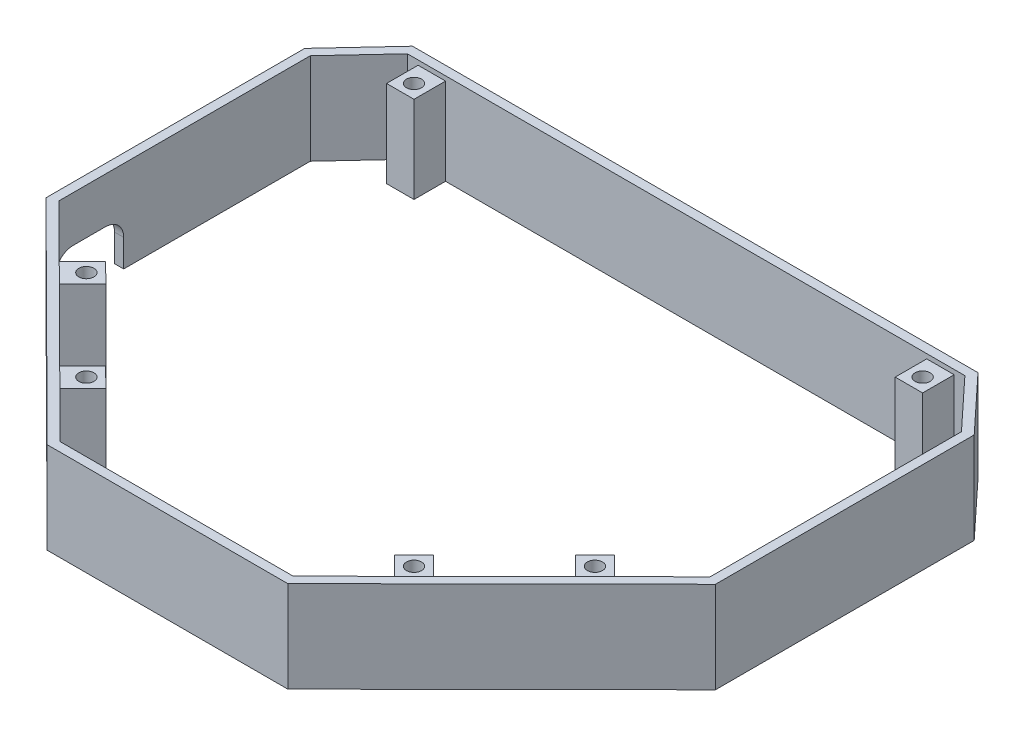
SolidWorks part; units mm, degrees
ref_plane "Front Plane" through (0, 0, 0) normal (0, 0, 1) x (1, 0, 0)
ref_plane "Top Plane" through (0, 0, 0) normal (0, 1, 0) x (1, 0, 0)
ref_plane "Right Plane" through (0, 0, 0) normal (1, 0, 0) x (0, 0, -1)
sketch "Sketch1" plane through (0, 0, 0) normal (0, 1, 0) x (1, 0, 0)
  line L0 (-61, 38.5) -> (61, 38.5)
  line L1 (-25.5, -73) -> (25.5, -73)
  line L2 (-25.5, -73) -> (-71.25, -27.5)
  line L3 (-71.25, -27.5) -> (-71.25, 27.5)
  line L4 (-71.25, 27.5) -> (-61, 38.5)
  line L5 (25.5, -73) -> (71.25, -27.5)
  line L6 (71.25, -27.5) -> (71.25, 27.5)
  line L7 (71.25, 27.5) -> (61, 38.5)
  line L8 (-61.8701, 40.5) -> (61.8701, 40.5)
  line L9 (61.8701, 40.5) -> (73.25, 28.2874)
  line L10 (73.25, 28.2874) -> (73.25, -28.3316)
  line L11 (73.25, -28.3316) -> (26.3252, -75)
  line L12 (26.3252, -75) -> (-26.3252, -75)
  line L13 (-26.3252, -75) -> (-73.25, -28.3316)
  line L14 (-73.25, -28.3316) -> (-73.25, 28.2874)
  line L15 (-73.25, 28.2874) -> (-61.8701, 40.5)
  point P2 (0, 38.5)
  point P6 (0, -73)
  point P22 (-71.25, 0)
  dimension "D1" = 122
  dimension "D2" = 51
  dimension "D3" = 111.5
  dimension "D4" = 55
  dimension "D5" = 55
  dimension "D6" = 142.5
  dimension "D7" = 11
  dimension "D8" = 11
  dimension "D9" = 71.25
  dimension "D10" = 2
  dimension "D11" = 2
  dimension "D12" = 2
  dimension "D13" = 2
  dimension "D14" = 2
  dimension "D15" = 2
  dimension "D16" = 2
  dimension "D17" = 2
extrude "Boss-Extrude1" add sketch "Sketch1" along normal blind 20
sketch "Sketch2" plane through (0, 0, 0) normal (0, 1, 0) x (1, 0, 0)
  line L1 (61, 38.5) -> (-61, 38.5) construction
  line L2 (-40.8804, -57.7037) -> (-35.8616, -52.6574)
  line L3 (-71.25, -27.5) -> (-25.5, -73) construction
  line L4 (-35.8616, -52.6574) -> (-31.6074, -56.8884)
  line L5 (-31.6074, -56.8884) -> (-36.6261, -61.9347)
  line L6 (-36.6261, -61.9347) -> (-40.8804, -57.7037)
  line L7 (-60.7345, -37.9581) -> (-55.6616, -32.8574)
  line L8 (-55.6616, -32.8574) -> (-51.4074, -37.0884)
  line L9 (-51.4074, -37.0884) -> (-56.4802, -42.1891)
  line L10 (-56.4802, -42.1891) -> (-60.7345, -37.9581)
  line L11 (0, -1000) -> (0, 49000) construction
  line L12 (-58.65, 38.5) -> (-52.65, 38.5)
  line L13 (-58.65, 38.5) -> (-58.65, 31.6)
  line L14 (-58.65, 31.6) -> (-52.65, 31.6)
  line L15 (-52.65, 38.5) -> (-52.65, 31.6)
  line L16 (52.65, 38.5) -> (52.65, 31.6)
  line L17 (58.65, 31.6) -> (52.65, 31.6)
  line L18 (58.65, 38.5) -> (58.65, 31.6)
  line L19 (58.65, 38.5) -> (52.65, 38.5)
  line L20 (56.4802, -42.1891) -> (60.7345, -37.9581)
  line L21 (51.4074, -37.0884) -> (56.4802, -42.1891)
  line L22 (55.6616, -32.8574) -> (51.4074, -37.0884)
  line L23 (60.7345, -37.9581) -> (55.6616, -32.8574)
  line L24 (36.6261, -61.9347) -> (40.8804, -57.7037)
  line L25 (31.6074, -56.8884) -> (36.6261, -61.9347)
  line L26 (35.8616, -52.6574) -> (31.6074, -56.8884)
  line L27 (40.8804, -57.7037) -> (35.8616, -52.6574)
  circle A0 centre (-55.65, -37.1) radius 1.65
  circle A1 centre (-35.85, -56.9) radius 1.65
  circle A3 centre (-55.65, 34.6) radius 1.65
  circle A4 centre (55.65, 34.6) radius 1.65
  circle A5 centre (35.85, -56.9) radius 1.65
  circle A6 centre (55.65, -37.1) radius 1.65
  dimension "D3" = 3.3
  dimension "D5" = 3.3
  dimension "D9" = 3.3
  dimension "D1" = 55.65
  dimension "D2" = 3.9
  dimension "D4" = 55.65
  dimension "D6" = 71.7
  dimension "D7" = 35.85
  dimension "D8" = 19.8
  dimension "D10" = 3
  dimension "D11" = 3
  dimension "D12" = 3
  dimension "D13" = 3
  dimension "D14" = 3
  dimension "D15" = 3
  dimension "D16" = 3
  dimension "D17" = 3
  dimension "D18" = 3
extrude "Boss-Extrude2" add sketch "Sketch2" along normal blind 19
sketch "Sketch3" plane through (-73.25, 0, 0) normal (-1, 0, 0) x (0, 0, 1)
  line L1 (28.3316, 0) -> (13.3316, 0)
  line L2 (28.3316, 0) -> (28.3316, 6)
  line L3 (24.3316, 10) -> (17.3316, 10)
  line L4 (13.3316, 0) -> (13.3316, 6)
  arc A0 (28.3316, 6) -> (24.3316, 10) centre (24.3316, 6) ccw
  arc A1 (17.3316, 10) -> (13.3316, 6) centre (17.3316, 6) ccw
  point P7 (28.3316, 10)
  point P10 (13.3316, 10)
  dimension "D3" = 4
  dimension "D1" = 15
  dimension "D2" = 10
extrude "Cut-Extrude1" cut sketch "Sketch3" against normal blind 10
